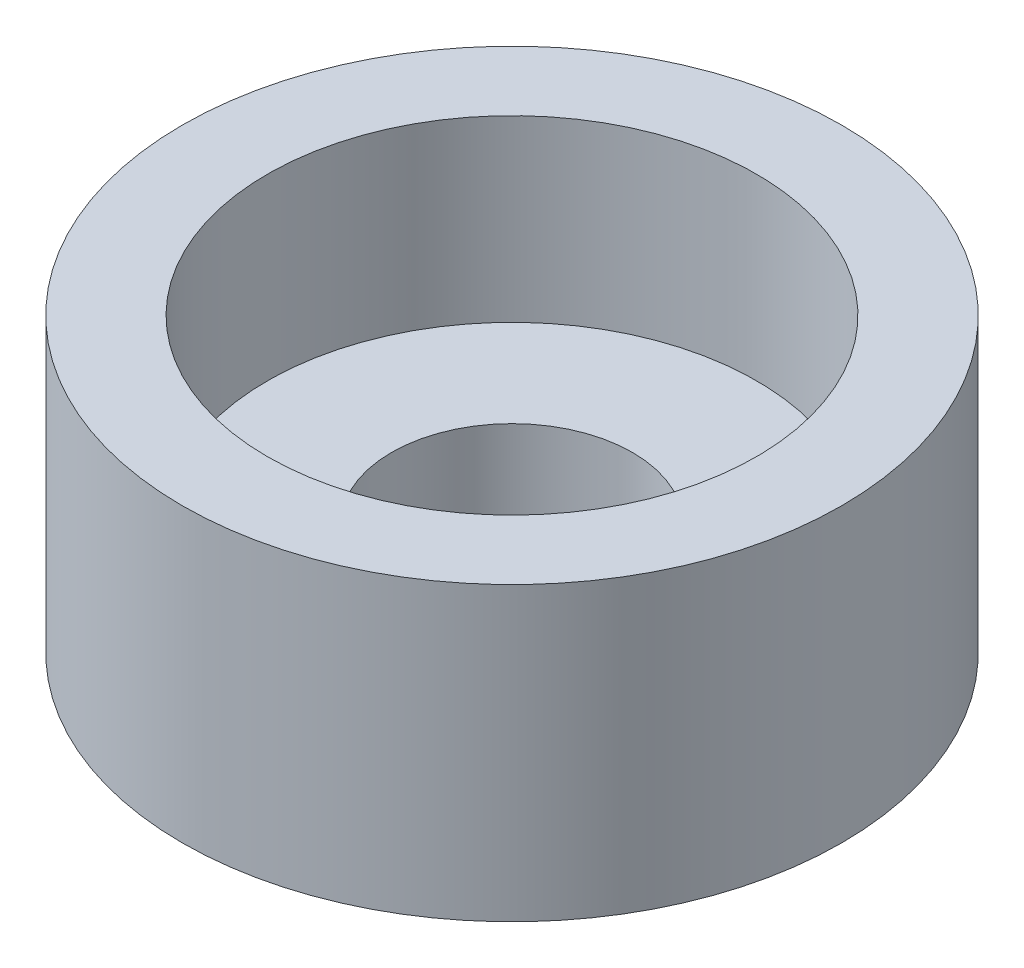
SolidWorks part; units mm, degrees
ref_plane "Front Plane" through (0, 0, 0) normal (0, 0, 1) x (1, 0, 0)
ref_plane "Top Plane" through (0, 0, 0) normal (0, 1, 0) x (1, 0, 0)
ref_plane "Right Plane" through (0, 0, 0) normal (1, 0, 0) x (0, 0, -1)
sketch "Sketch1" plane through (0, 0, 0) normal (0, 1, 0) x (1, 0, 0)
  circle A0 centre (0, 0) radius 35
  circle A1 centre (0, 0) radius 12.8
  dimension "D1" = 70
  dimension "D2" = 25.6
extrude "Boss-Extrude1" add sketch "Sketch1" along normal blind 31
sketch "Sketch4" plane through (0, 31, 0) normal (0, 1, 0) x (1, 0, 0)
  circle A0 centre (0, 0) radius 25.97
  dimension "D1" = 51.94
extrude "Cut-Extrude3" cut sketch "Sketch4" against normal blind 19
sketch "Sketch10" plane through (0, 0, 0) normal (0, -1, 0) x (1, 0, 0)
  line L0 (0, 0) -> (11.4907, 22.6522)
  line L1 (0, 0) -> (13.8721, -21.2774)
  line L2 (0, 0) -> (-25.3628, -1.3749)
  circle A0 centre (0, 0) radius 25.4
  circle A1 centre (-25.3628, -1.3749) radius 2.125
  circle A2 centre (11.4907, 22.6522) radius 2.125
  circle A3 centre (13.8721, -21.2774) radius 2.125
  dimension "D1" = 120
  dimension "D3" = 4.25
  dimension "D4" = 4.25
  dimension "D5" = 4.25
  dimension "D6" = 50.8
  dimension "D2" = 120
  dimension "D7" = 25.3628
extrude "Cut-Extrude6" cut sketch "Sketch10" against normal blind 5.1 contours A0 A1 | L2 A1 A0 | A0 A1 L2 | A0 A2 L0 | L0 A2 A0 | A0 A2 | L1 A3 A0 | A0 A3 L1 | A0 A3
